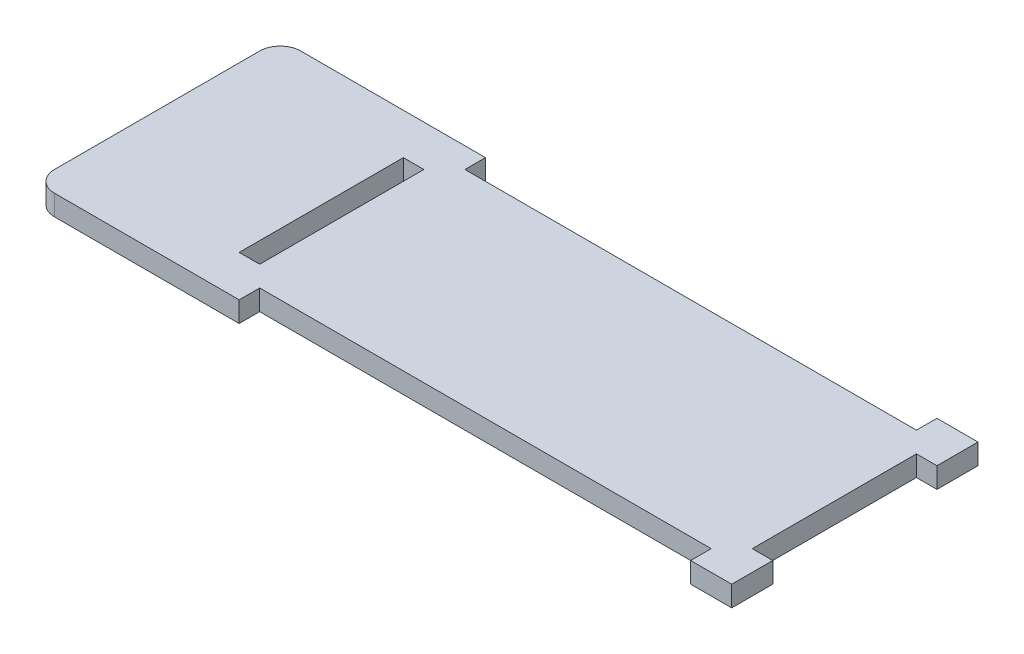
SolidWorks part; units mm, degrees
ref_plane "Front Plane" through (0, 0, 0) normal (0, 0, 1) x (1, 0, 0)
ref_plane "Top Plane" through (0, 0, 0) normal (0, 1, 0) x (1, 0, 0)
ref_plane "Right Plane" through (0, 0, 0) normal (1, 0, 0) x (0, 0, -1)
sketch "Sketch1" plane through (0, 0, 0) normal (0, 1, 0) x (1, 0, 0)
  line L0 (-57.15, 38.1) -> (-57.15, -38.1) construction
  line L1 (-101.6, -38.1) -> (-44.45, -38.1)
  line L2 (-107.95, -31.75) -> (-107.95, 31.75)
  line L3 (-101.6, 38.1) -> (-44.45, 38.1)
  line L4 (107.95, -38.1) -> (107.95, -25.4)
  line L5 (-107.95, -38.1) -> (107.95, 38.1) construction
  line L6 (-107.95, 38.1) -> (107.95, -38.1) construction
  line L7 (107.95, 25.4) -> (107.95, 38.1)
  line L8 (-57.15, 25.4) -> (-50.8, 25.4)
  line L9 (-57.15, 25.4) -> (-57.15, -25.4)
  line L10 (-57.15, -25.4) -> (-50.8, -25.4)
  line L11 (-50.8, 25.4) -> (-50.8, -25.4)
  line L12 (107.95, 25.4) -> (101.6, 25.4)
  line L13 (95.25, 38.1) -> (107.95, 38.1)
  line L14 (107.95, -25.4) -> (101.6, -25.4)
  line L15 (101.6, 25.4) -> (101.6, -25.4)
  line L17 (-44.45, -38.1) -> (-44.45, -31.75)
  line L18 (-44.45, -31.75) -> (95.25, -31.75)
  line L19 (95.25, -38.1) -> (95.25, -31.75)
  line L20 (95.25, -38.1) -> (107.95, -38.1)
  line L21 (-44.45, 38.1) -> (-44.45, 31.75)
  line L22 (-44.45, 31.75) -> (95.25, 31.75)
  line L23 (95.25, 38.1) -> (95.25, 31.75)
  arc A0 (-101.6, -38.1) -> (-107.95, -31.75) centre (-101.6, -31.75) cw
  arc A1 (-107.95, 31.75) -> (-101.6, 38.1) centre (-101.6, 31.75) cw
  point P0 (0, 0)
  dimension "D3" = 6.35
  dimension "D1" = 76.2
  dimension "D2" = 215.9
  dimension "D4" = 50.8
  dimension "D5" = 12.7
  dimension "D6" = 12.7
  dimension "D7" = 6.35
  dimension "D8" = 6.35
  dimension "D9" = 12.7
  dimension "D10" = 12.7
  dimension "D11" = 12.7
  dimension "D12" = 12.7
  dimension "D13" = 6.35
extrude "Boss-Extrude1" add sketch "Sketch1" along normal mid plane 6.35
